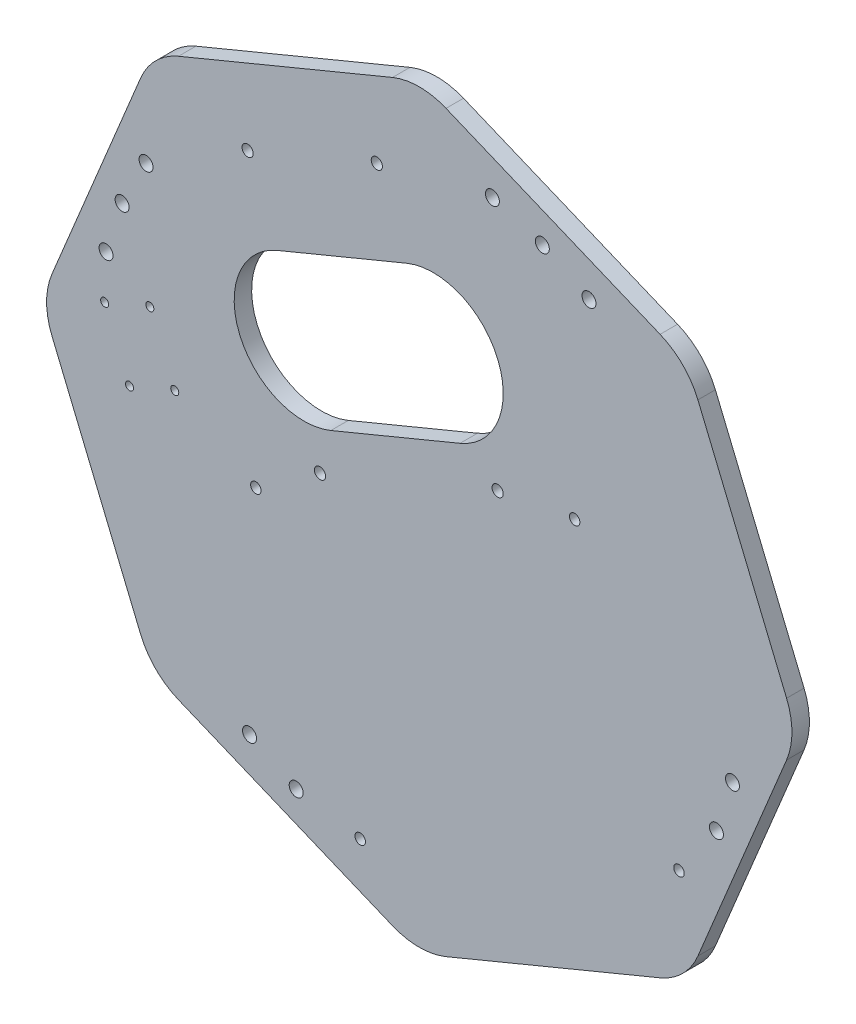
SolidWorks part; units mm, degrees
ref_plane "前视基准面" through (0, 0, 0) normal (0, 0, 1) x (1, 0, 0)
ref_plane "上视基准面" through (0, 0, 0) normal (0, 1, 0) x (1, 0, 0)
ref_plane "右视基准面" through (0, 0, 0) normal (1, 0, 0) x (0, 0, -1)
sketch "草图1" plane through (0, 0, 0) normal (0, 0, 1) x (1, 0, 0)
  line L0 (0, 121.5223) -> (0, -117.9323) construction
  line L1 (-126.6637, 0) -> (129.3981, 0) construction
  line L2 (0, 108.2392) -> (-76.5367, 76.5367)
  line L3 (-76.5367, 76.5367) -> (-108.2392, 0)
  line L4 (-108.2392, 0) -> (-76.5367, -76.5367)
  line L5 (-76.5367, -76.5367) -> (0, -108.2392)
  line L6 (0, -108.2392) -> (76.5367, -76.5367)
  line L7 (76.5367, -76.5367) -> (108.2392, 0)
  line L8 (108.2392, 0) -> (76.5367, 76.5367)
  line L9 (76.5367, 76.5367) -> (0, 108.2392)
  line L10 (-46.7415, -16.1138) -> (-16.8922, -88.1764) construction
  line L11 (-46.7415, -16.1138) -> (44.4454, 21.6571) construction
  line L12 (-16.8922, -88.1764) -> (74.2947, -50.4055) construction
  line L13 (44.4454, 21.6571) -> (74.2947, -50.4055) construction
  line L14 (-38.2683, -92.388) -> (38.2683, 92.388) construction
  line L15 (-92.388, 38.2683) -> (92.388, -38.2683) construction
  line L16 (-56.0214, 63.3866) -> (-28.3916, -3.3175) construction
  line L17 (-56.0214, 63.3866) -> (-5.208, 84.4342) construction
  line L18 (-28.3916, -3.3175) -> (22.4218, 17.7301) construction
  line L19 (-5.208, 84.4342) -> (22.4218, 17.7301) construction
  line L20 (-38.2683, 92.388) -> (0, 0) construction
  line L21 (-89.9912, 8.208) -> (-82.8733, -8.9762) construction
  line L22 (-89.9912, 8.208) -> (-77.0569, 13.5656) construction
  line L23 (-82.8733, -8.9762) -> (-69.939, -3.6186) construction
  line L24 (-77.0569, 13.5656) -> (-69.939, -3.6186) construction
  line L25 (-32.943, 27.269) -> (4.0122, 42.5763) construction
  line L26 (-40.5967, 45.7466) -> (-3.6415, 61.0539)
  line L27 (-25.2894, 8.7914) -> (11.6658, 24.0987)
  circle A0 centre (0, 0) radius 100 construction
  circle A1 centre (-46.7415, -16.1138) radius 1.5
  circle A2 centre (-16.8922, -88.1764) radius 1.5
  circle A3 centre (74.2947, -50.4055) radius 1.5
  circle A4 centre (44.4454, 21.6571) radius 1.5
  circle A5 centre (-35.2069, -84.9969) radius 2
  circle A6 centre (84.9969, -35.2069) radius 2
  circle A7 centre (35.2069, 84.9969) radius 2
  circle A8 centre (-84.9969, 35.2069) radius 2
  circle A11 centre (22.4218, 17.7301) radius 1.6
  circle A12 centre (-28.3916, -3.3175) radius 1.6
  circle A13 centre (-49.0923, 66.2567) radius 1.6
  circle A14 centre (-12.1371, 81.564) radius 1.6
  circle A15 centre (-89.9912, 8.208) radius 1.15
  circle A16 centre (-77.0569, 13.5656) radius 1.15
  circle A17 centre (-69.939, -3.6186) radius 1.15
  circle A18 centre (-82.8733, -8.9762) radius 1.15
  arc A19 (-40.5967, 45.7466) -> (-25.2894, 8.7914) centre (-32.943, 27.269) ccw
  arc A20 (11.6658, 24.0987) -> (-3.6415, 61.0539) centre (4.0122, 42.5763) ccw
  circle A21 centre (48.551, 78.146) radius 2
  circle A22 centre (20.9269, 89.5883) radius 2
  circle A24 centre (89.5883, -20.9269) radius 2
  circle A25 centre (-48.551, -78.146) radius 2
  circle A27 centre (-78.146, 48.551) radius 2
  circle A28 centre (-89.5883, 20.9269) radius 2
  circle A29 centre (-20.9269, -89.5883) radius 2 [skipped]
  circle A30 centre (78.146, -48.551) radius 2 [skipped]
  point P56 (-14.4654, 34.9226)
  point P80 (0, 0)
  dimension "D6" = 3
  dimension "D7" = 3
  dimension "D8" = 3
  dimension "D9" = 3
  dimension "D10" = 4
  dimension "D11" = 4
  dimension "D12" = 4
  dimension "D13" = 4
  dimension "D14" = 8
  dimension "D15" = 8
  dimension "D16" = 8
  dimension "D17" = 8
  dimension "D21" = 20
  dimension "D22" = 20
  dimension "D23" = 3.2
  dimension "D24" = 3.2
  dimension "D26" = 3.2
  dimension "D27" = 3.2
  dimension "D31" = 2.3
  dimension "D32" = 2.3
  dimension "D33" = 2.3
  dimension "D34" = 2.3
  dimension "D38" = 20
  dimension "D41" = 15
  dimension "D42" = 4
  dimension "D43" = 92
  dimension "D44" = 15
  dimension "D45" = 4
  dimension "D1" = 200
  dimension "D2" = 78
  dimension "D3" = 98.7
  dimension "D4" = 50.65
  dimension "D5" = 25
  dimension "D18" = 72.2
  dimension "D19" = 55
  dimension "D20" = 27.5
  dimension "D25" = 20
  dimension "D28" = 18.6
  dimension "D29" = 14
  dimension "D30" = 20
  dimension "D35" = 18
  dimension "D36" = 0
  dimension "D37" = 40
  dimension "D39" = 10
  dimension "D40" = 92
  dimension "D46" = 4
extrude "凸台-拉伸1" add sketch "草图1" along normal blind 5
fillet "圆角1" radius 20 8 edges at (-76.5367, 76.5367, 2.5) (0, 108.2392, 2.5) (76.5367, 76.5367, 2.5) (108.2392, 0, 2.5) (76.5367, -76.5367, 2.5) (0, -108.2392, 2.5) (-76.5367, -76.5367, 2.5) (-108.2392, 0, 2.5)
